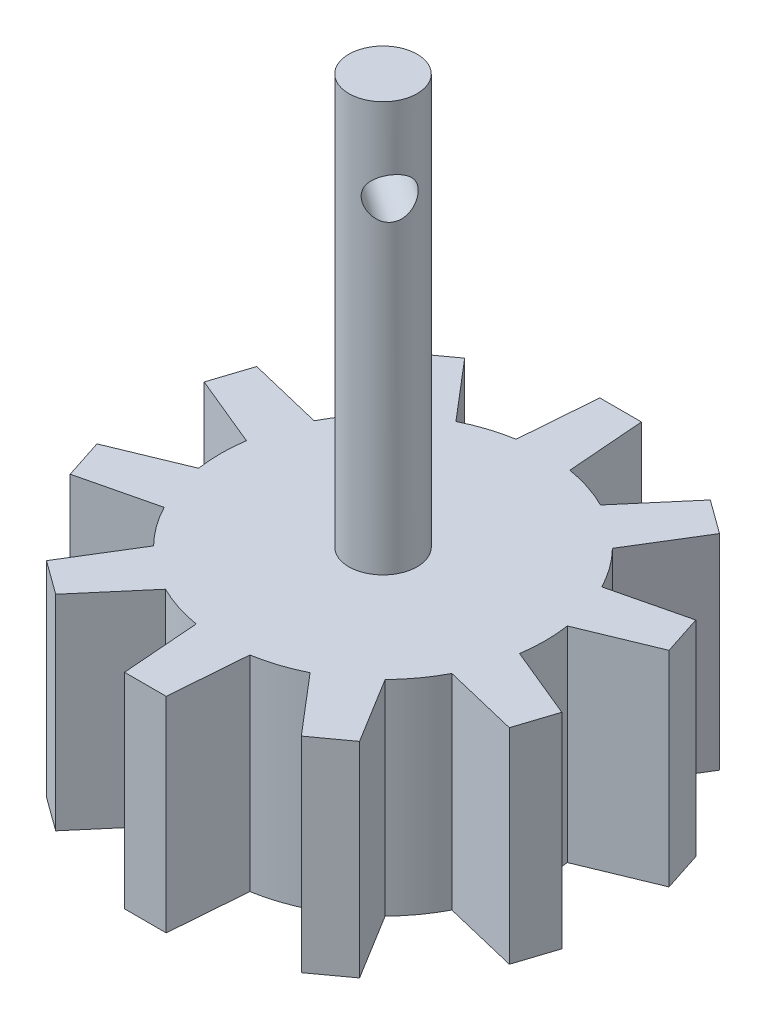
SolidWorks part; units mm, degrees
material "Free-Cutting Brass, UNS C36000"
ref_plane "Front Plane" through (0, 0, 0) normal (0, 0, 1) x (1, 0, 0)
ref_plane "Top Plane" through (0, 0, 0) normal (0, 1, 0) x (1, 0, 0)
ref_plane "Right Plane" through (0, 0, 0) normal (1, 0, 0) x (0, 0, -1)
sketch "Sketch1" plane through (0, 0, 0) normal (0, 1, 0) x (1, 0, 0)
  circle A0 centre (0, 0) radius 4.75
  dimension "D1" = 9.5
extrude "GEAR_ROOT" add sketch "Sketch1" along normal blind 6
sketch "Sketch3" plane through (0, 0, 0) normal (0, 1, 0) x (1, 0, 0)
  circle A0 centre (0, 0) radius 1
  dimension "D1" = 2
extrude "NEEDLE_SHAFT" add sketch "Sketch3" along normal blind 18
sketch "Sketch6" plane through (0, 0, 0) normal (0, -1, 0) x (1, 0, 0)
  line L0 (0, 4.75) -> (0, 9.0508) construction
  line L1 (0.61, 6.9576) -> (-0.61, 6.9576)
  line L2 (-0.61, 6.9576) -> (-0.7864, 4.6844)
  line L3 (0.61, 6.9576) -> (0.7864, 4.6844)
  line L4 (4.5831, 5.2703) -> (3.5961, 5.9874)
  line L5 (3.5961, 5.9874) -> (2.1172, 4.252)
  line L6 (4.5831, 5.2703) -> (3.3897, 3.3276)
  line L7 (6.8056, 1.5699) -> (6.4286, 2.7302)
  line L8 (6.4286, 2.7302) -> (4.2122, 2.1955)
  line L9 (6.8056, 1.5699) -> (4.6982, 0.6997)
  line L10 (6.4286, -2.7302) -> (6.8056, -1.5699)
  line L11 (6.8056, -1.5699) -> (4.6982, -0.6997)
  line L12 (6.4286, -2.7302) -> (4.2122, -2.1955)
  line L13 (3.5961, -5.9874) -> (4.5831, -5.2703)
  line L14 (4.5831, -5.2703) -> (3.3897, -3.3276)
  line L15 (3.5961, -5.9874) -> (2.1172, -4.252)
  line L16 (-0.61, -6.9576) -> (0.61, -6.9576)
  line L17 (0.61, -6.9576) -> (0.7864, -4.6844)
  line L18 (-0.61, -6.9576) -> (-0.7864, -4.6844)
  line L19 (-4.5831, -5.2703) -> (-3.5961, -5.9874)
  line L20 (-3.5961, -5.9874) -> (-2.1172, -4.252)
  line L21 (-4.5831, -5.2703) -> (-3.3897, -3.3276)
  line L22 (-6.8056, -1.5699) -> (-6.4286, -2.7302)
  line L23 (-6.4286, -2.7302) -> (-4.2122, -2.1955)
  line L24 (-6.8056, -1.5699) -> (-4.6982, -0.6997)
  line L25 (-6.4286, 2.7302) -> (-6.8056, 1.5699)
  line L26 (-6.8056, 1.5699) -> (-4.6982, 0.6997)
  line L27 (-6.4286, 2.7302) -> (-4.2122, 2.1955)
  line L28 (-3.5961, 5.9874) -> (-4.5831, 5.2703)
  line L29 (-4.5831, 5.2703) -> (-3.3897, 3.3276)
  line L30 (-3.5961, 5.9874) -> (-2.1172, 4.252)
  circle A0 centre (0, 0) radius 4.75 construction
  arc A1 (-0.7864, 4.6844) -> (0.7864, 4.6844) centre (0, 0) cw
  arc A2 (2.1172, 4.252) -> (3.3897, 3.3276) centre (0, 0) cw
  arc A3 (4.2122, 2.1955) -> (4.6982, 0.6997) centre (0, 0) cw
  arc A4 (4.6982, -0.6997) -> (4.2122, -2.1955) centre (0, 0) cw
  arc A5 (3.3897, -3.3276) -> (2.1172, -4.252) centre (0, 0) cw
  arc A6 (0.7864, -4.6844) -> (-0.7864, -4.6844) centre (0, 0) cw
  arc A7 (-2.1172, -4.252) -> (-3.3897, -3.3276) centre (0, 0) cw
  arc A8 (-4.2122, -2.1955) -> (-4.6982, -0.6997) centre (0, 0) cw
  arc A9 (-4.6982, 0.6997) -> (-4.2122, 2.1955) centre (0, 0) cw
  arc A10 (-3.3897, 3.3276) -> (-2.1172, 4.252) centre (0, 0) cw
  circle A11 centre (0, 0) radius 4.75 construction
  point P8 (0, 6.9576)
  point P58 (0, 0)
  dimension "D3" = 10
  dimension "D1" = 1.22
  dimension "D2" = 2.28
  dimension "D4" = 0.7864
  dimension "D5" = 9.0508
extrude "Boss-Extrude1" add sketch "Sketch6" against normal up to surface (6 mm away) up to face at (0, 6, 1)
ref_plane "Plane1" through (1.2288, 0, 0.8603) normal (0.8192, 0, 0.5735) x (0.5735, 0, -0.8192)
sketch "Sketch7" plane through (1.2288, 0, 0.8603) normal (0.8192, 0, 0.5735) x (0.5735, 0, -0.8192)
  circle A0 centre (0, 15.5346) radius 0.6
  dimension "D1" = 1.2
extrude "Cut-Extrude1" cut sketch "Sketch7" against normal blind 10
